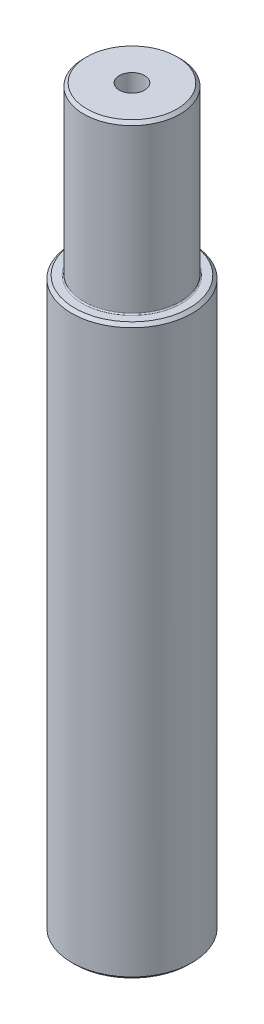
SolidWorks part; units mm, degrees
ref_plane "Front" through (0, 0, 0) normal (0, 0, 1) x (1, 0, 0)
ref_plane "Top" through (0, 0, 0) normal (0, 1, 0) x (1, 0, 0)
ref_plane "Right" through (0, 0, 0) normal (1, 0, 0) x (0, 0, -1)
sketch "Sketch1" plane through (0, 0, 0) normal (0, 0, 1) x (1, 0, 0)
  line L0 (0, 7.4762) -> (0, -8.3651) construction
  line L1 (0, 0) -> (10, 0)
  line L2 (10, 0) -> (10, 94.35)
  line L3 (10, 94.35) -> (8, 94.35)
  line L4 (8, 94.35) -> (8, 122)
  line L5 (8, 122) -> (0, 122)
  line L6 (0, 122) -> (0, 0)
  dimension "D1" = 94.35
  dimension "D2" = 122
  dimension "D3" = 8
  dimension "D4" = 2
revolve "Revolve1" add sketch "Sketch1" angle 360 about L0
hole_wizard "M5 Tapped Hole1" positions "Sketch2" profile "Sketch4" tap size "M5" standard "ISO"
sketch "Sketch2" plane through (0, 0, 0) normal (0, -1, 0) x (-1, 0, 0)
  point P0 (0, 0)
sketch "Sketch4" plane through (0, 0, 0) normal (1, 0, 0) x (0, 0, -1)
  line L0 (0, 0) -> (0, 13.6618)
  line L1 (0, 13.6618) -> (2.1, 12.4)
  line L2 (2.1, 12.4) -> (2.1, 0)
  line L5 (2.1, 0) -> (0, 0)
  line L10 (0, 13.6618) -> (-2.1, 12.4) construction
  line L11 (0, -6.35) -> (0, 107.95) construction
  dimension "Tap Drill Dia." = 4.2
  dimension "Tap Drill Depth" = 12.4
  dimension "Drill Angle" = 118
cosmetic thread "Hole Thread1" parameters "D1"=10, "D2"=5
ref_plane "Plane1" through (0, 61, 0) normal (0, -1, 0) x (-1, 0, 0)
mirror "Mirror1" about plane through (0, 61, 0) normal (0, -1, 0) of "M5 Tapped Hole1"
cosmetic thread "Hole Thread2" parameters "D1"=10, "D2"=5
fillet "Fillet1" radius 0.2 1 edges at (0, 94.35, 8)
chamfer "Chamfer1" distance 0.5 angle 45 3 edges at (0, 0, 10) (0, 94.35, 10) (0, 122, 8)
